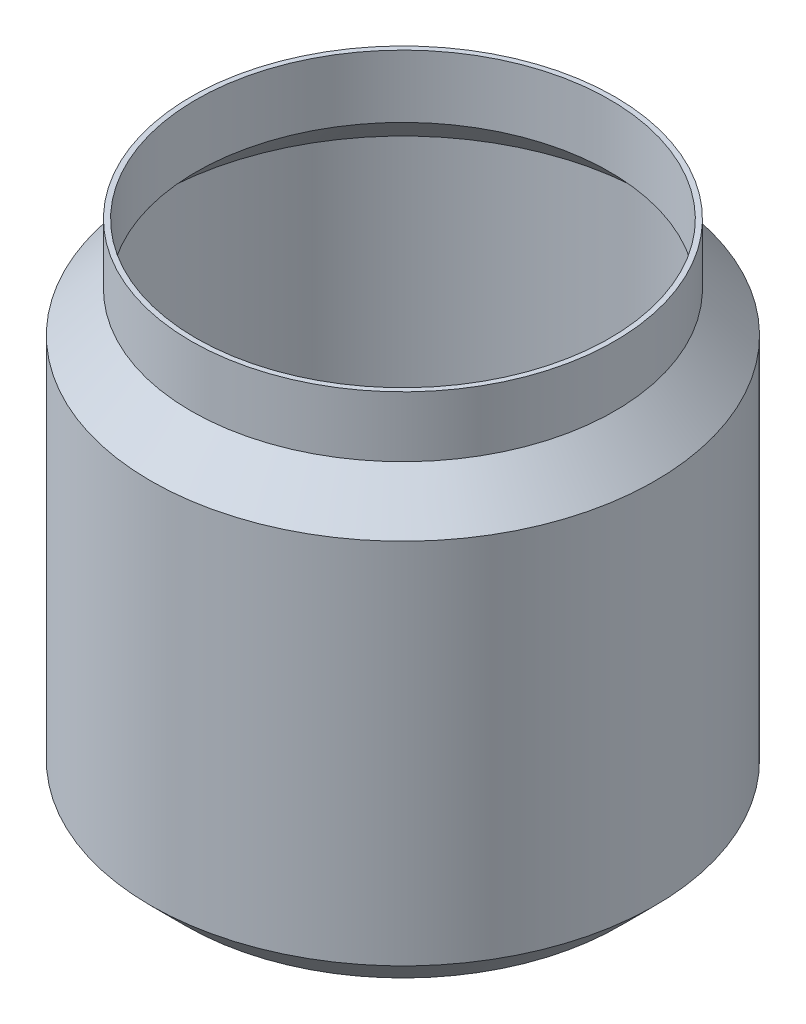
SolidWorks part; units mm, degrees
ref_plane "Plan de face" through (0, 0, 0) normal (0, 0, 1) x (1, 0, 0)
ref_plane "Plan de dessus" through (0, 0, 0) normal (0, 1, 0) x (1, 0, 0)
ref_plane "Plan de droite" through (0, 0, 0) normal (1, 0, 0) x (0, 0, -1)
ref_axis "Axe1" through (0, 105, 0) along (0, -1, 0)
sketch "Esquisse2" plane through (0, 0, 0) normal (0, 0, 1) x (1, 0, 0)
  line L0 (0, 0) -> (42.9289, 0)
  line L1 (42.9289, 0) -> (50, 7.0711)
  line L2 (50, 7.0711) -> (50, 80)
  line L3 (50, 80) -> (42, 88)
  line L4 (42, 88) -> (42, 100)
  line L5 (42, 100) -> (41, 100)
  line L6 (0, 1) -> (42.5147, 1)
  line L7 (42.5147, 1) -> (49, 7.4853)
  line L8 (49, 7.4853) -> (49, 79.5858)
  line L9 (49, 79.5858) -> (41, 87.5858)
  line L12 (0, 1) -> (0, 0)
  line L13 (41, 100) -> (41, 87.5858)
  line L14 (42, 100) -> (12.0292, 52.5458) construction
  line L15 (41, 96.544) -> (12.8747, 52.0118) construction
  line L16 (41, 87.5858) -> (41, 96.544) construction
  point P15 (0, 0)
  point P17 (50, 77.4286)
  dimension "D2" = 12
  dimension "D3" = 100
  dimension "D4" = 50
  dimension "D5" = 10
  dimension "D6" = 42
  dimension "D7" = 135
  dimension "D1" = 1
revolve "Révolution1" add sketch "Esquisse2" angle 360 about axis through (0, 105, 0) along (0, -1, 0)
